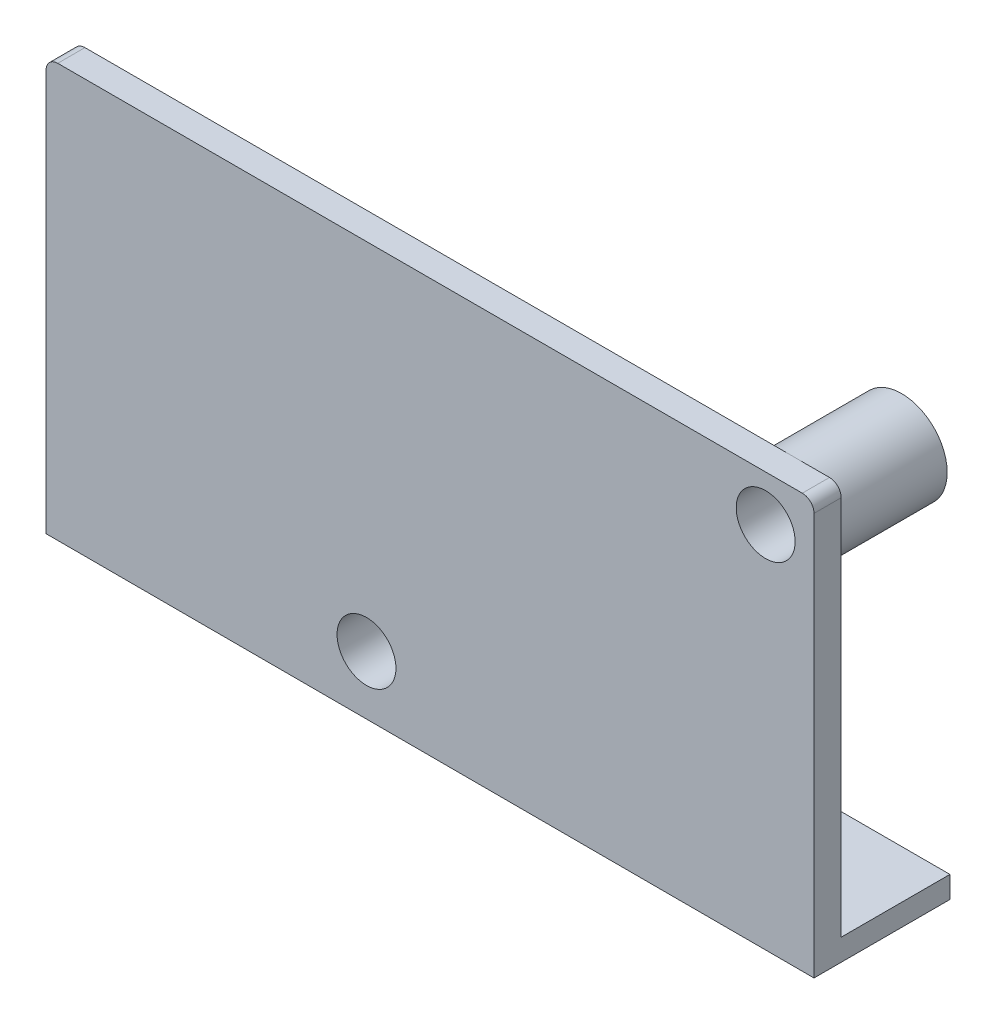
SolidWorks part; units mm, degrees
ref_plane "前视基准面" through (0, 0, 0) normal (0, 0, 1) x (1, 0, 0)
ref_plane "上视基准面" through (0, 0, 0) normal (0, 1, 0) x (1, 0, 0)
ref_plane "右视基准面" through (0, 0, 0) normal (1, 0, 0) x (0, 0, -1)
sketch "草图2" plane through (0, 0, 0) normal (0, 0, 1) x (1, 0, 0)
  line L0 (33.2419, -17.3338) -> (33.2419, -5.4548)
  line L4 (33.2419, -5.4548) -> (33.2419, 25.6013)
  line L5 (-36.2952, -18.4088) -> (32.1669, -18.4088)
  line L6 (-36.2952, 26.6762) -> (32.1669, 26.6762)
  line L7 (-37.3701, -17.3338) -> (-37.3701, 25.6013)
  line L8 (-37.3701, -11.3206) -> (33.2419, -11.3943)
  line L2616 (29.2206, 25.1602) -> (28.7969, 25.1936)
  line L2617 (28.7969, 25.1936) -> (28.3732, 25.1602)
  line L2618 (28.3732, 25.1602) -> (27.96, 25.061)
  line L2619 (27.96, 25.061) -> (27.5673, 24.8984)
  line L2620 (27.5673, 24.8984) -> (27.2049, 24.6763)
  line L2621 (27.2049, 24.6763) -> (26.8818, 24.4003)
  line L2622 (26.8818, 24.4003) -> (26.6058, 24.0772)
  line L2623 (26.6058, 24.0772) -> (26.3837, 23.7148)
  line L2624 (26.3837, 23.7148) -> (26.2211, 23.3222)
  line L2625 (26.2211, 23.3222) -> (26.1219, 22.9089)
  line L2626 (26.1219, 22.9089) -> (26.0885, 22.4852)
  line L2627 (26.0885, 22.4852) -> (26.1219, 22.0616)
  line L2628 (26.1219, 22.0616) -> (26.2211, 21.6483)
  line L2629 (26.2211, 21.6483) -> (26.3837, 21.2557)
  line L2630 (26.3837, 21.2557) -> (26.6058, 20.8933)
  line L2631 (26.6058, 20.8933) -> (26.8818, 20.5701)
  line L2632 (26.8818, 20.5701) -> (27.2049, 20.2941)
  line L2633 (27.2049, 20.2941) -> (27.5673, 20.0721)
  line L2634 (27.5673, 20.0721) -> (27.96, 19.9094)
  line L2635 (27.96, 19.9094) -> (28.3732, 19.8102)
  line L2636 (28.3732, 19.8102) -> (28.7969, 19.7769)
  line L2637 (28.7969, 19.7769) -> (29.2206, 19.8102)
  line L2638 (29.2206, 19.8102) -> (29.6338, 19.9094)
  line L2639 (29.6338, 19.9094) -> (30.0264, 20.0721)
  line L2640 (30.0264, 20.0721) -> (30.3888, 20.2941)
  line L2641 (30.3888, 20.2941) -> (30.712, 20.5701)
  line L2642 (30.712, 20.5701) -> (30.988, 20.8933)
  line L2643 (30.988, 20.8933) -> (31.21, 21.2557)
  line L2644 (31.21, 21.2557) -> (31.3727, 21.6483)
  line L2645 (31.3727, 21.6483) -> (31.4719, 22.0616)
  line L2646 (31.4719, 22.0616) -> (31.5052, 22.4852)
  line L2647 (31.5052, 22.4852) -> (31.4719, 22.9089)
  line L2648 (31.4719, 22.9089) -> (31.3727, 23.3222)
  line L2649 (31.3727, 23.3222) -> (31.21, 23.7148)
  line L2650 (31.21, 23.7148) -> (30.988, 24.0772)
  line L2651 (30.988, 24.0772) -> (30.712, 24.4003)
  line L2652 (30.712, 24.4003) -> (30.3888, 24.6763)
  line L2653 (30.3888, 24.6763) -> (30.0264, 24.8984)
  line L2654 (30.0264, 24.8984) -> (29.6338, 25.061)
  line L2655 (29.6338, 25.061) -> (29.2206, 25.1602)
  line L2808 (-6.6331, -8.3493) -> (-6.3142, -8.1539)
  line L2809 (-6.3142, -8.1539) -> (-5.991, -7.8779)
  line L2810 (-5.991, -7.8779) -> (-5.715, -7.5547)
  line L2811 (-5.715, -7.5547) -> (-5.493, -7.1923)
  line L2812 (-5.493, -7.1923) -> (-5.3303, -6.7997)
  line L2813 (-5.3303, -6.7997) -> (-5.2311, -6.3864)
  line L2814 (-5.2311, -6.3864) -> (-5.1978, -5.9628)
  line L2815 (-5.1978, -5.9628) -> (-5.2311, -5.5391)
  line L2816 (-5.2311, -5.5391) -> (-5.3303, -5.1258)
  line L2817 (-5.3303, -5.1258) -> (-5.493, -4.7332)
  line L2818 (-5.493, -4.7332) -> (-5.715, -4.3708)
  line L2819 (-5.715, -4.3708) -> (-5.991, -4.0477)
  line L2820 (-5.991, -4.0477) -> (-6.3142, -3.7717)
  line L2821 (-6.3142, -3.7717) -> (-6.6766, -3.5496)
  line L2822 (-6.6766, -3.5496) -> (-7.0692, -3.387)
  line L2823 (-7.0692, -3.387) -> (-7.4824, -3.2878)
  line L2824 (-7.4824, -3.2878) -> (-7.9061, -3.2544)
  line L2825 (-7.9061, -3.2544) -> (-8.3298, -3.2878)
  line L2826 (-8.3298, -3.2878) -> (-8.743, -3.387)
  line L2827 (-8.743, -3.387) -> (-9.1357, -3.5496)
  line L2828 (-9.1357, -3.5496) -> (-9.4981, -3.7717)
  line L2829 (-9.4981, -3.7717) -> (-9.8212, -4.0477)
  line L2830 (-9.8212, -4.0477) -> (-10.0972, -4.3708)
  line L2831 (-10.0972, -4.3708) -> (-10.3193, -4.7332)
  line L2832 (-10.3193, -4.7332) -> (-10.4819, -5.1258)
  line L2833 (-10.4819, -5.1258) -> (-10.5811, -5.5391)
  line L2834 (-10.5811, -5.5391) -> (-10.6145, -5.9628)
  line L2835 (-10.6145, -5.9628) -> (-10.5811, -6.3864)
  line L2836 (-10.5811, -6.3864) -> (-10.4819, -6.7997)
  line L2837 (-10.4819, -6.7997) -> (-10.3193, -7.1923)
  line L2838 (-10.3193, -7.1923) -> (-10.0972, -7.5547)
  line L2839 (-10.0972, -7.5547) -> (-9.8212, -7.8779)
  line L2840 (-9.8212, -7.8779) -> (-9.4981, -8.1539)
  line L2841 (-9.4981, -8.1539) -> (-9.1792, -8.3493)
  line L3455 (29.2206, 25.1602) -> (28.7969, 25.1936)
  line L3456 (28.7969, 25.1936) -> (28.3732, 25.1602)
  line L3457 (28.3732, 25.1602) -> (27.96, 25.061)
  line L3458 (27.96, 25.061) -> (27.5673, 24.8984)
  line L3459 (27.5673, 24.8984) -> (27.2049, 24.6763)
  line L3460 (27.2049, 24.6763) -> (26.8818, 24.4003)
  line L3461 (26.8818, 24.4003) -> (26.6058, 24.0772)
  line L3462 (26.6058, 24.0772) -> (26.3837, 23.7148)
  line L3463 (26.3837, 23.7148) -> (26.2211, 23.3222)
  line L3464 (26.2211, 23.3222) -> (26.1219, 22.9089)
  line L3465 (26.1219, 22.9089) -> (26.0885, 22.4852)
  line L3466 (26.0885, 22.4852) -> (26.1219, 22.0616)
  line L3467 (26.1219, 22.0616) -> (26.2211, 21.6483)
  line L3468 (26.2211, 21.6483) -> (26.3837, 21.2557)
  line L3469 (26.3837, 21.2557) -> (26.6058, 20.8933)
  line L3470 (26.6058, 20.8933) -> (26.8818, 20.5701)
  line L3471 (26.8818, 20.5701) -> (27.2049, 20.2941)
  line L3472 (27.2049, 20.2941) -> (27.5673, 20.0721)
  line L3473 (27.5673, 20.0721) -> (27.96, 19.9094)
  line L3474 (27.96, 19.9094) -> (28.3732, 19.8102)
  line L3475 (28.3732, 19.8102) -> (28.7969, 19.7769)
  line L3476 (28.7969, 19.7769) -> (29.2206, 19.8102)
  line L3477 (29.2206, 19.8102) -> (29.6338, 19.9094)
  line L3478 (29.6338, 19.9094) -> (30.0264, 20.0721)
  line L3479 (30.0264, 20.0721) -> (30.3888, 20.2941)
  line L3480 (30.3888, 20.2941) -> (30.712, 20.5701)
  line L3481 (30.712, 20.5701) -> (30.988, 20.8933)
  line L3482 (30.988, 20.8933) -> (31.21, 21.2557)
  line L3483 (31.21, 21.2557) -> (31.3727, 21.6483)
  line L3484 (31.3727, 21.6483) -> (31.4719, 22.0616)
  line L3485 (31.4719, 22.0616) -> (31.5052, 22.4852)
  line L3486 (31.5052, 22.4852) -> (31.4719, 22.9089)
  line L3487 (31.4719, 22.9089) -> (31.3727, 23.3222)
  line L3488 (31.3727, 23.3222) -> (31.21, 23.7148)
  line L3489 (31.21, 23.7148) -> (30.988, 24.0772)
  line L3490 (30.988, 24.0772) -> (30.712, 24.4003)
  line L3491 (30.712, 24.4003) -> (30.3888, 24.6763)
  line L3492 (30.3888, 24.6763) -> (30.0264, 24.8984)
  line L3493 (30.0264, 24.8984) -> (29.6338, 25.061)
  line L3494 (29.6338, 25.061) -> (29.2206, 25.1602)
  line L4236 (-7.4824, -3.2878) -> (-7.9061, -3.2544)
  line L4237 (-7.9061, -3.2544) -> (-8.3298, -3.2878)
  line L4238 (-8.3298, -3.2878) -> (-8.743, -3.387)
  line L4239 (-8.743, -3.387) -> (-9.1357, -3.5496)
  line L4240 (-9.1357, -3.5496) -> (-9.4981, -3.7717)
  line L4241 (-9.4981, -3.7717) -> (-9.8212, -4.0477)
  line L4242 (-9.8212, -4.0477) -> (-10.0972, -4.3708)
  line L4243 (-10.0972, -4.3708) -> (-10.3193, -4.7332)
  line L4244 (-10.3193, -4.7332) -> (-10.4819, -5.1258)
  line L4245 (-10.4819, -5.1258) -> (-10.5811, -5.5391)
  line L4246 (-10.5811, -5.5391) -> (-10.6145, -5.9628)
  line L4247 (-10.6145, -5.9628) -> (-10.5811, -6.3864)
  line L4248 (-10.5811, -6.3864) -> (-10.4819, -6.7997)
  line L4249 (-10.4819, -6.7997) -> (-10.3193, -7.1923)
  line L4250 (-10.3193, -7.1923) -> (-10.0972, -7.5547)
  line L4251 (-10.0972, -7.5547) -> (-9.8212, -7.8779)
  line L4252 (-9.8212, -7.8779) -> (-9.4981, -8.1539)
  line L4253 (-9.4981, -8.1539) -> (-9.1357, -8.3759)
  line L4254 (-9.1357, -8.3759) -> (-8.743, -8.5386)
  line L4255 (-8.743, -8.5386) -> (-8.3298, -8.6378)
  line L4256 (-8.3298, -8.6378) -> (-7.9061, -8.6711)
  line L4257 (-7.9061, -8.6711) -> (-7.4824, -8.6378)
  line L4258 (-7.4824, -8.6378) -> (-7.0692, -8.5386)
  line L4259 (-7.0692, -8.5386) -> (-6.6766, -8.3759)
  line L4260 (-6.6766, -8.3759) -> (-6.3142, -8.1539)
  line L4261 (-6.3142, -8.1539) -> (-5.991, -7.8779)
  line L4262 (-5.991, -7.8779) -> (-5.715, -7.5547)
  line L4263 (-5.715, -7.5547) -> (-5.493, -7.1923)
  line L4264 (-5.493, -7.1923) -> (-5.3303, -6.7997)
  line L4265 (-5.3303, -6.7997) -> (-5.2311, -6.3864)
  line L4266 (-5.2311, -6.3864) -> (-5.1978, -5.9628)
  line L4267 (-5.1978, -5.9628) -> (-5.2311, -5.5391)
  line L4268 (-5.2311, -5.5391) -> (-5.3303, -5.1258)
  line L4269 (-5.3303, -5.1258) -> (-5.493, -4.7332)
  line L4270 (-5.493, -4.7332) -> (-5.715, -4.3708)
  line L4271 (-5.715, -4.3708) -> (-5.991, -4.0477)
  line L4272 (-5.991, -4.0477) -> (-6.3142, -3.7717)
  line L4273 (-6.3142, -3.7717) -> (-6.6766, -3.5496)
  line L4274 (-6.6766, -3.5496) -> (-7.0692, -3.387)
  line L4275 (-7.0692, -3.387) -> (-7.4824, -3.2878)
  line L6751 (-40.2351, 12.9602) -> (-37.3701, 12.9602)
  line L6763 (-40.2351, 4.0702) -> (-37.3701, 4.1337)
  line L6764 (-40.2351, 4.0702) -> (-40.2351, 12.9602)
  circle A1 centre (33.2419, -5.4548) radius 0.04
  circle A3 centre (33.2419, -5.4548) radius 0.04
  circle A7 centre (33.2419, -5.4548) radius 0.04
  circle A8 centre (33.2419, -5.4548) radius 0.04
  arc A1492 (32.1669, -18.4088) -> (33.2419, -17.3338) centre (32.1669, -17.3338) ccw
  arc A1495 (33.2419, 25.6013) -> (32.1669, 26.6762) centre (32.1669, 25.6013) ccw
  arc A1498 (-36.2952, 26.6762) -> (-37.3701, 25.6013) centre (-36.2952, 25.6013) ccw
  arc A1501 (-37.3701, -17.3338) -> (-36.2952, -18.4088) centre (-36.2952, -17.3338) ccw
  circle A1904 centre (28.7969, 22.4852) radius 1.25
  circle A1905 centre (28.7969, 22.4852) radius 1.3008
  circle A1906 centre (28.7969, 22.4852) radius 1.25
  circle A1907 centre (28.7969, 22.4852) radius 1.25
  circle A1908 centre (28.7969, 22.4852) radius 1.3008
  circle A1909 centre (28.7969, 22.4852) radius 0.8
  circle A1910 centre (-7.9061, -5.9628) radius 1.25
  circle A1911 centre (-7.9061, -5.9628) radius 1.3008
  circle A1912 centre (-7.9061, -5.9628) radius 1.25
  circle A1913 centre (-7.9061, -5.9628) radius 1.25
  circle A1914 centre (-7.9061, -5.9628) radius 1.3008
  circle A1915 centre (-7.9061, -5.9628) radius 0.8
  circle A2317 centre (32.4709, 10.6882) radius 0.0635
  circle A2321 centre (32.4709, 10.6882) radius 0.0635
  circle A3495 centre (-40.2351, 12.9602) radius 0.0381
  circle A3503 centre (-37.3701, 4.1337) radius 0.0381
  circle A3517 centre (-37.3701, 4.1337) radius 0.0381
  circle A3521 centre (-40.2351, 4.0702) radius 0.0381
  circle A3522 centre (-37.3701, 4.1337) radius 0.0381
  circle A3523 centre (-40.2351, 4.0702) radius 0.0381
  circle A3524 centre (-40.2351, 12.9602) radius 0.0381
  circle A3525 centre (-36.7351, 11.6902) radius 0.0381
  circle A3529 centre (-36.7351, 5.3402) radius 0.0381
  point P2 (0, 0)
  dimension "D1" = 70.612
  dimension "D2" = 45.085
sketch "草图3" plane through (0, 0, 0) normal (0, 0, 1) x (1, 0, 0)
  line L0 (-36.2952, 26.6762) -> (32.1669, 26.6762)
  line L1 (33.2419, 25.6013) -> (33.2419, -11.3943)
  line L2 (33.2419, -5.4548) -> (33.2419, 25.6013) construction
  line L3 (-37.3701, -11.3206) -> (33.2419, -11.3943)
  line L4 (-37.3701, -11.3206) -> (-37.3701, 25.6013)
  arc A0 (-37.3701, 25.6013) -> (-36.2952, 26.6762) centre (-36.2952, 25.6013) cw
  arc A1 (32.1669, 26.6762) -> (33.2419, 25.6013) centre (32.1669, 25.6013) cw
extrude "凸台-拉伸1" add sketch "草图3" against normal blind 2.5
sketch "草图4" plane through (0, 0, -2.5) normal (0, 0, -1) x (-1, 0, 0)
  line L0 (37.3701, 25.6013) -> (37.3701, -11.3206) construction
  line L1 (37.3701, -9.3943) -> (-33.2419, -9.3943)
  line L2 (37.3701, -9.3943) -> (37.3701, -11.3943)
  line L3 (37.3701, -11.3943) -> (-33.2419, -11.3943)
  line L4 (-33.2419, -9.3943) -> (-33.2419, -11.3943)
  dimension "D1" = 2
extrude "凸台-拉伸2" add sketch "草图4" along normal blind 10
sketch "草图5" plane through (0, 0, 0) normal (0, 0, 1) x (1, 0, 0)
  circle A0 centre (-7.9061, -5.9628) radius 4.19
  circle A1 centre (28.7969, 22.4852) radius 4.191
extrude "凸台-拉伸3" add sketch "草图5" against normal blind 12.5
sketch "草图7" plane through (0, 0, 0) normal (0, 0, 1) x (1, 0, 0)
  circle A0 centre (-7.9061, -5.9628) radius 2.7083
  circle A1 centre (28.7969, 22.4852) radius 2.7083
extrude "切除-拉伸1" cut sketch "草图7" against normal blind 10.5
sketch "草图8" plane through (0, 0, -12.5) normal (0, 0, -1) x (-1, 0, 0)
  circle A0 centre (-28.7969, 22.4852) radius 1.65
  circle A1 centre (7.9061, -5.9628) radius 1.65
extrude "切除-拉伸2" cut sketch "草图8" against normal through all both and the other way through all
